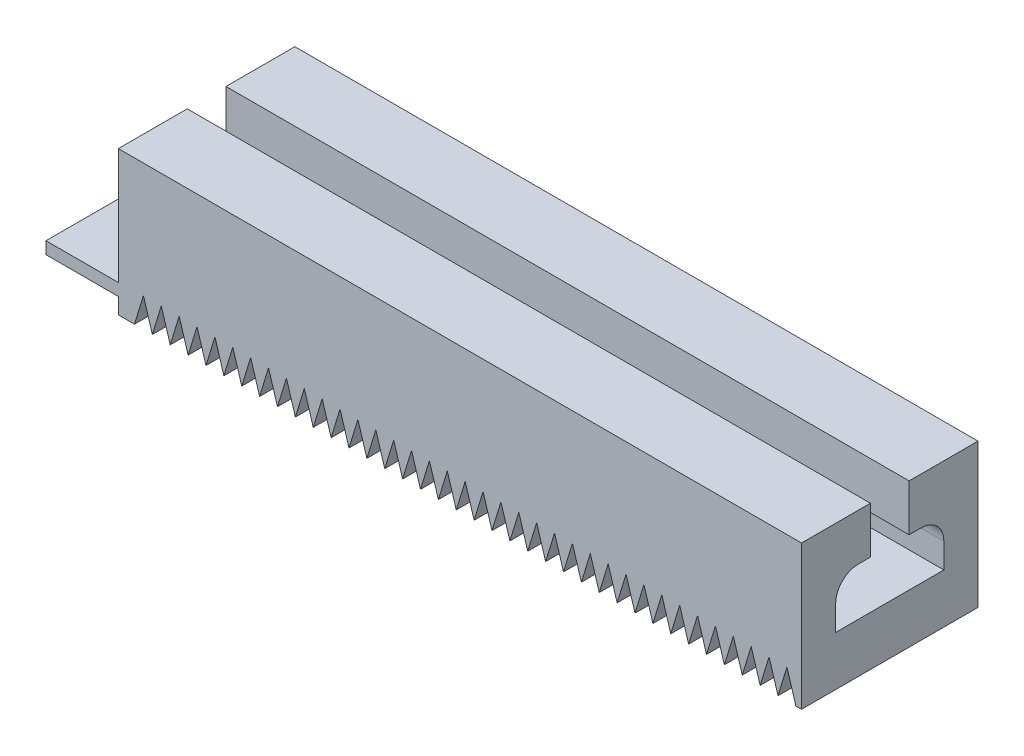
SolidWorks part; units mm, degrees
ref_plane "Front Plane" through (0, 0, 0) normal (0, 0, 1) x (1, 0, 0)
ref_plane "Top Plane" through (0, 0, 0) normal (0, 1, 0) x (1, 0, 0)
ref_plane "Right Plane" through (0, 0, 0) normal (1, 0, 0) x (0, 0, -1)
sketch "Sketch1" plane through (0, 0, 0) normal (0, 0, 1) x (1, 0, 0)
  line L0 (-67.3997, -32.3763) -> (-67.2447, -32.3763)
  line L1 (-70.2297, -19.7263) -> (-10.2297, -19.7263)
  line L2 (-70.2297, -19.7263) -> (-70.2297, -32.3763)
  line L3 (-70.2297, -32.3763) -> (-68.8147, -32.3763)
  line L4 (-10.2297, -19.7263) -> (-10.2297, -32.3763)
  line L5 (-68.8147, -32.3763) -> (-68.0297, -29.8019)
  line L6 (-68.0297, -29.8019) -> (-67.2447, -32.3763)
  line L7 (-67.2447, -32.3763) -> (-66.4597, -29.8019)
  line L8 (-66.4597, -29.8019) -> (-65.6747, -32.3763)
  line L9 (-65.6747, -32.3763) -> (-64.8897, -29.8019)
  line L10 (-64.8897, -29.8019) -> (-64.1047, -32.3763)
  line L11 (-64.1047, -32.3763) -> (-63.3197, -29.8019)
  line L12 (-63.3197, -29.8019) -> (-62.5347, -32.3763)
  line L13 (-62.5347, -32.3763) -> (-61.7497, -29.8019)
  line L14 (-61.7497, -29.8019) -> (-60.9647, -32.3763)
  line L15 (-60.9647, -32.3763) -> (-60.1797, -29.8019)
  line L16 (-60.1797, -29.8019) -> (-59.3947, -32.3763)
  line L17 (-59.3947, -32.3763) -> (-58.6097, -29.8019)
  line L18 (-58.6097, -29.8019) -> (-57.8247, -32.3763)
  line L19 (-57.8247, -32.3763) -> (-57.0397, -29.8019)
  line L20 (-57.0397, -29.8019) -> (-56.2547, -32.3763)
  line L21 (-56.2547, -32.3763) -> (-55.4697, -29.8019)
  line L22 (-55.4697, -29.8019) -> (-54.6847, -32.3763)
  line L23 (-54.6847, -32.3763) -> (-53.8997, -29.8019)
  line L24 (-53.8997, -29.8019) -> (-53.1147, -32.3763)
  line L25 (-53.1147, -32.3763) -> (-52.3297, -29.8019)
  line L26 (-52.3297, -29.8019) -> (-51.5447, -32.3763)
  line L27 (-51.5447, -32.3763) -> (-50.7597, -29.8019)
  line L28 (-50.7597, -29.8019) -> (-49.9747, -32.3763)
  line L29 (-49.9747, -32.3763) -> (-49.1897, -29.8019)
  line L30 (-49.1897, -29.8019) -> (-48.4047, -32.3763)
  line L31 (-48.4047, -32.3763) -> (-47.6197, -29.8019)
  line L32 (-47.6197, -29.8019) -> (-46.8347, -32.3763)
  line L33 (-46.8347, -32.3763) -> (-46.0497, -29.8019)
  line L34 (-46.0497, -29.8019) -> (-45.2647, -32.3763)
  line L35 (-45.2647, -32.3763) -> (-44.4797, -29.8019)
  line L36 (-44.4797, -29.8019) -> (-43.6947, -32.3763)
  line L37 (-43.6947, -32.3763) -> (-42.9097, -29.8019)
  line L38 (-42.9097, -29.8019) -> (-42.1247, -32.3763)
  line L39 (-42.1247, -32.3763) -> (-41.3397, -29.8019)
  line L40 (-41.3397, -29.8019) -> (-40.5547, -32.3763)
  line L41 (-40.5547, -32.3763) -> (-39.7697, -29.8019)
  line L42 (-39.7697, -29.8019) -> (-38.9847, -32.3763)
  line L43 (-38.9847, -32.3763) -> (-38.1997, -29.8019)
  line L44 (-38.1997, -29.8019) -> (-37.4147, -32.3763)
  line L45 (-37.4147, -32.3763) -> (-36.6297, -29.8019)
  line L46 (-36.6297, -29.8019) -> (-35.8447, -32.3763)
  line L47 (-35.8447, -32.3763) -> (-35.0597, -29.8019)
  line L48 (-35.0597, -29.8019) -> (-34.2747, -32.3763)
  line L49 (-34.2747, -32.3763) -> (-33.4897, -29.8019)
  line L50 (-33.4897, -29.8019) -> (-32.7047, -32.3763)
  line L51 (-32.7047, -32.3763) -> (-31.9197, -29.8019)
  line L52 (-31.9197, -29.8019) -> (-31.1347, -32.3763)
  line L53 (-31.1347, -32.3763) -> (-30.3497, -29.8019)
  line L54 (-76.5857, -29.9133) -> (-70.2297, -29.9133)
  line L55 (-30.3497, -29.8019) -> (-29.5647, -32.3763)
  line L56 (-29.5647, -32.3763) -> (-28.7797, -29.8019)
  line L57 (-28.7797, -29.8019) -> (-27.9947, -32.3763)
  line L58 (-27.9947, -32.3763) -> (-27.2097, -29.8019)
  line L59 (-27.2097, -29.8019) -> (-26.4247, -32.3763)
  line L60 (-26.4247, -32.3763) -> (-25.6397, -29.8019)
  line L61 (-13.6597, -32.3763) -> (-13.6314, -32.4052)
  line L62 (-25.6397, -29.8019) -> (-24.8547, -32.3763)
  line L63 (-24.8547, -32.3763) -> (-24.0697, -29.8019)
  line L64 (-10.7247, -32.3763) -> (-10.2297, -32.3763)
  line L65 (-76.5857, -29.9133) -> (-76.5857, -30.9766)
  line L66 (-76.5857, -30.9766) -> (-70.2297, -30.9766)
  line L67 (-24.0697, -29.8019) -> (-23.2847, -32.3763)
  line L70 (-23.2847, -32.3763) -> (-22.4997, -29.8019)
  line L71 (-22.4997, -29.8019) -> (-21.7147, -32.3763)
  line L72 (-21.7147, -32.3763) -> (-20.9297, -29.8019)
  line L73 (-20.9297, -29.8019) -> (-20.1447, -32.3763)
  line L74 (-20.1447, -32.3763) -> (-19.3597, -29.8019)
  line L75 (-19.3597, -29.8019) -> (-18.5747, -32.3763)
  line L76 (-18.5747, -32.3763) -> (-17.7897, -29.8019)
  line L77 (-17.7897, -29.8019) -> (-17.0047, -32.3763)
  line L78 (-17.0047, -32.3763) -> (-16.2197, -29.8019)
  line L79 (-16.2197, -29.8019) -> (-15.4347, -32.3763)
  line L80 (-15.4347, -32.3763) -> (-14.6497, -29.8019)
  line L81 (-14.6497, -29.8019) -> (-13.8647, -32.3763)
  line L82 (-13.8647, -32.3763) -> (-13.0797, -29.8019)
  line L83 (-13.0797, -29.8019) -> (-12.2947, -32.3763)
  line L84 (-12.2947, -32.3763) -> (-11.5097, -29.8019)
  line L85 (-11.5097, -29.8019) -> (-10.7247, -32.3763)
  line L87 (-13.8647, -32.3763) -> (-13.6597, -32.3763)
  point P86 (-70.2297, -28.0263)
  dimension "D1" = 60
  dimension "D2" = 12.65
  dimension "D3" = 1.57
  dimension "D5" = 8.3
extrude "Boss-Extrude1" add sketch "Sketch1" along normal blind 15.5 contours L84 L85 L64 L4 L1 L2 L3 L5 L6 L7 L8 L9 L10 L11 L12 L13 L14 L15 L16 L17 L18 L19 L20 L21 L22 L23 L24 L25 L26 L27 L28 L29 L30 L31 L32 L33 L34 L35 L36 L37 L38 L39 L40 L41 L42 L43 L44 L45 L46 | L65 L66 L2 L54
sketch "Sketch2" plane through (-70.2297, 0, 0) normal (-1, 0, 0) x (0, 0, 1)
  line L3 (6.05, -23.8263) -> (5, -23.8263)
  line L4 (3, -25.8263) -> (3, -28.0263)
  line L5 (3, -28.0263) -> (12.5, -28.0263)
  line L6 (12.5, -28.0263) -> (12.5, -25.8263)
  line L7 (10.5, -23.8263) -> (9.45, -23.8263)
  line L9 (9.45, -19.7263) -> (6.05, -19.7263)
  line L10 (6.05, -23.8263) -> (6.05, -19.7263)
  line L11 (9.45, -23.8263) -> (9.45, -19.7263)
  arc A0 (12.5, -25.8263) -> (10.5, -23.8263) centre (10.5, -25.8263) ccw
  arc A1 (5, -23.8263) -> (3, -25.8263) centre (5, -25.8263) ccw
  dimension "D1" = 2
extrude "Cut-Extrude1" cut sketch "Sketch2" against normal blind 81.5
